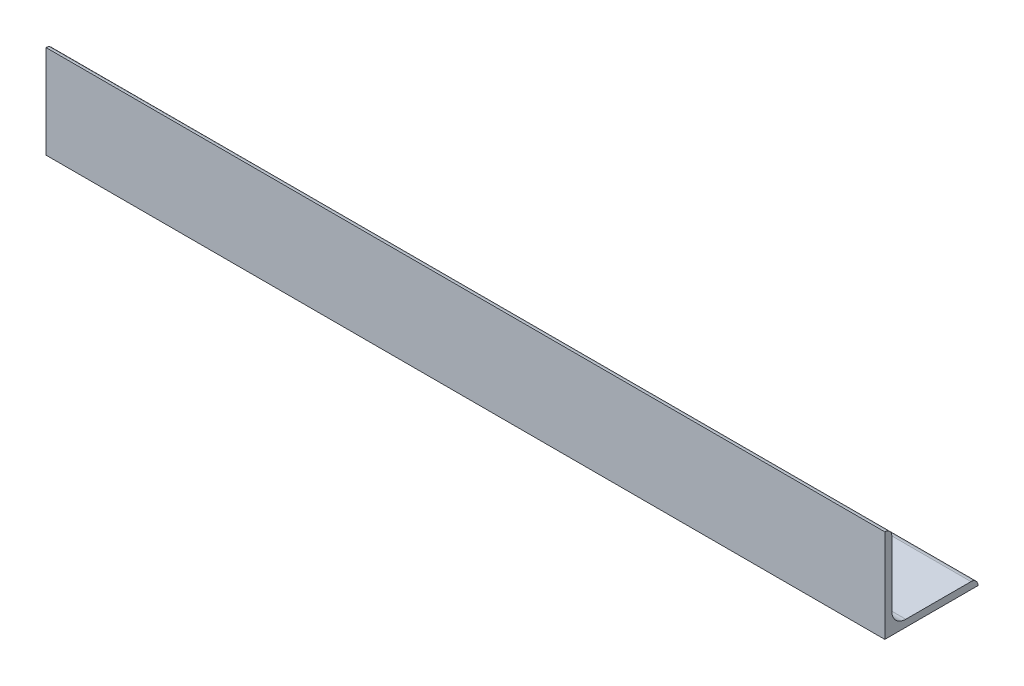
SolidWorks part; units mm, degrees
ref_plane "Front Plane" through (0, 0, 0) normal (0, 0, 1) x (1, 0, 0)
ref_plane "Top Plane" through (0, 0, 0) normal (0, 1, 0) x (1, 0, 0)
ref_plane "Right Plane" through (0, 0, 0) normal (1, 0, 0) x (0, 0, -1)
sketch "Sketch1" plane through (0, 0, 0) normal (0, 1, 0) x (1, 0, 0)
  line L0 (0, 0) -> (360, 0)
  dimension "D1" = 360
other "L angle (equal) 40X40X3(11)"
ref_plane "Plane1" through (0, 0, 0) normal (1, 0, 0) x (0, 0, -1)
sketch "Sketch13" plane through (0, 0, 0) normal (1, 0, 0) x (0, 0, -1)
  line L0 (0, 40) -> (0, 0)
  line L2 (3, 37) -> (3, 9)
  line L3 (9, 3) -> (37, 3)
  line L5 (40, 0) -> (0, 0)
  arc A0 (3, 37) -> (0, 40) centre (0, 37) ccw
  arc A1 (40, 0) -> (37, 3) centre (37, 0) ccw
  arc A2 (9, 3) -> (3, 9) centre (9, 9) cw
  point P8 (0, 20)
  point P9 (20, 0)
  point P10 (0, 0)
  dimension "Radius_2" = 3
  dimension "Radius_1" = 6
  dimension "V_leg" = 40
  dimension "H_leg" = 40
  dimension "thickness" = 3
